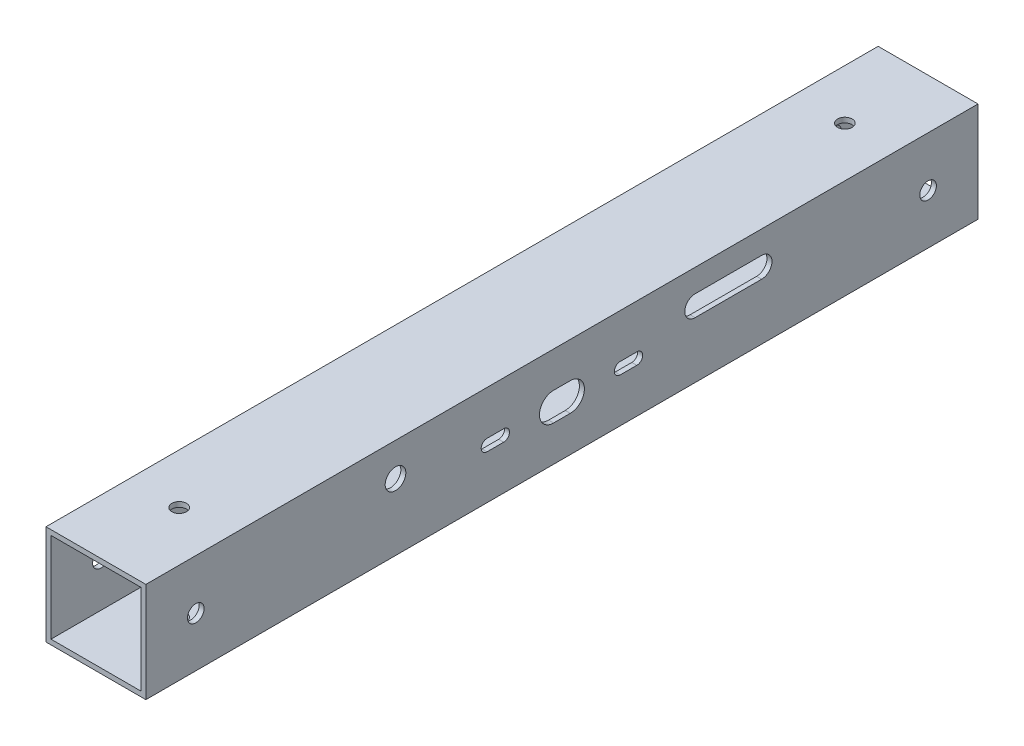
SolidWorks part; units mm, degrees
ref_plane "Front Plane" through (0, 0, 0) normal (0, 0, 1) x (1, 0, 0)
ref_plane "Top Plane" through (0, 0, 0) normal (0, 1, 0) x (1, 0, 0)
ref_plane "Right Plane" through (0, 0, 0) normal (1, 0, 0) x (0, 0, -1)
sketch "Sketch1" plane through (0, 0, 0) normal (0, 0, 1) x (1, 0, 0)
  line L1 (0, 0) -> (30, 0)
  line L2 (0, 0) -> (0, 30)
  line L3 (0, 30) -> (30, 30)
  line L4 (30, 0) -> (30, 30)
  line L5 (1.5, 1.5) -> (28.5, 1.5)
  line L6 (1.5, 1.5) -> (1.5, 28.5)
  line L7 (1.5, 28.5) -> (28.5, 28.5)
  line L8 (28.5, 1.5) -> (28.5, 28.5)
  dimension "D1" = 30
  dimension "D2" = 1.5
  dimension "D3" = 1.5
  dimension "D4" = 1.5
  dimension "D5" = 1.5
  dimension "D6" = 30
extrude "Boss-Extrude1" add sketch "Sketch1" along normal blind 250
sketch "Sketch2" plane through (30, 0, 0) normal (1, 0, 0) x (0, 0, -1)
  line L0 (-250, 0) -> (0, 0) construction
  line L1 (0, 0) -> (0, 30) construction
  line L2 (-250, 0) -> (-250, 30) construction
  line L3 (-142.5, 16.75) -> (-147.5, 16.75)
  line L4 (-142.5, 13.25) -> (-147.5, 13.25)
  line L5 (-107.5, 16.75) -> (-102.5, 16.75)
  line L6 (-107.5, 13.25) -> (-102.5, 13.25)
  line L7 (-125, 19.25) -> (-127.5, 19.25)
  line L8 (-125, 19.25) -> (-122.5, 19.25)
  line L9 (-125, 10.75) -> (-122.5, 10.75)
  line L10 (-125, 10.75) -> (-127.5, 10.75)
  line L13 (-75, 23.1) -> (-85, 23.1)
  line L14 (-75, 23.1) -> (-65, 23.1)
  line L15 (-75, 16.9) -> (-85, 16.9)
  line L16 (-75, 16.9) -> (-65, 16.9)
  circle A1 centre (-75, 20) radius 3.1 construction
  circle A2 centre (-15, 15) radius 2.5
  circle A3 centre (-235, 15) radius 2.5
  arc A4 (-142.5, 13.25) -> (-142.5, 16.75) centre (-142.5, 15) ccw
  circle A5 centre (-125, 15) radius 4.25 construction
  arc A6 (-107.5, 16.75) -> (-107.5, 13.25) centre (-107.5, 15) ccw
  arc A7 (-147.5, 16.75) -> (-147.5, 13.25) centre (-147.5, 15) ccw
  arc A8 (-102.5, 16.75) -> (-102.5, 13.25) centre (-102.5, 15) cw
  arc A9 (-127.5, 19.25) -> (-127.5, 10.75) centre (-127.5, 15) ccw
  arc A10 (-122.5, 19.25) -> (-122.5, 10.75) centre (-122.5, 15) cw
  circle A12 centre (-175, 20) radius 3.1
  arc A13 (-85, 23.1) -> (-85, 16.9) centre (-85, 20) ccw
  arc A14 (-65, 23.1) -> (-65, 16.9) centre (-65, 20) cw
  dimension "D2" = 6.2
  dimension "D7" = 5
  dimension "D10" = 5
  dimension "D14" = 8.5
  dimension "D15" = 3.5
  dimension "D16" = 3.5
  dimension "D24" = 6.2
  dimension "D3" = 20
  dimension "D4" = 20
  dimension "D5" = 100
  dimension "D6" = 75
  dimension "D8" = 15
  dimension "D9" = 15
  dimension "D11" = 15
  dimension "D12" = 15
  dimension "D13" = 15
  dimension "D17" = 17.5
  dimension "D18" = 17.5
  dimension "D19" = 125
  dimension "D20" = 5
  dimension "D21" = 5
  dimension "D22" = 2.5
  dimension "D23" = 2.5
  dimension "D25" = 10
  dimension "D26" = 10
extrude "Cut-Extrude1" cut sketch "Sketch2" against normal through all
sketch "Sketch3" plane through (0, 30, 0) normal (0, 1, 0) x (1, 0, 0)
  line L0 (30, 0) -> (0, 0) construction
  line L1 (30, -250) -> (30, 0) construction
  line L2 (30, -250) -> (0, -250) construction
  circle A0 centre (15, -25) radius 2.2
  circle A1 centre (15, -225) radius 2.2
  dimension "D1" = 4.4
  dimension "D2" = 4.4
  dimension "D3" = 25
  dimension "D4" = 15
  dimension "D5" = 25
extrude "Cut-Extrude2" cut sketch "Sketch3" against normal through all
